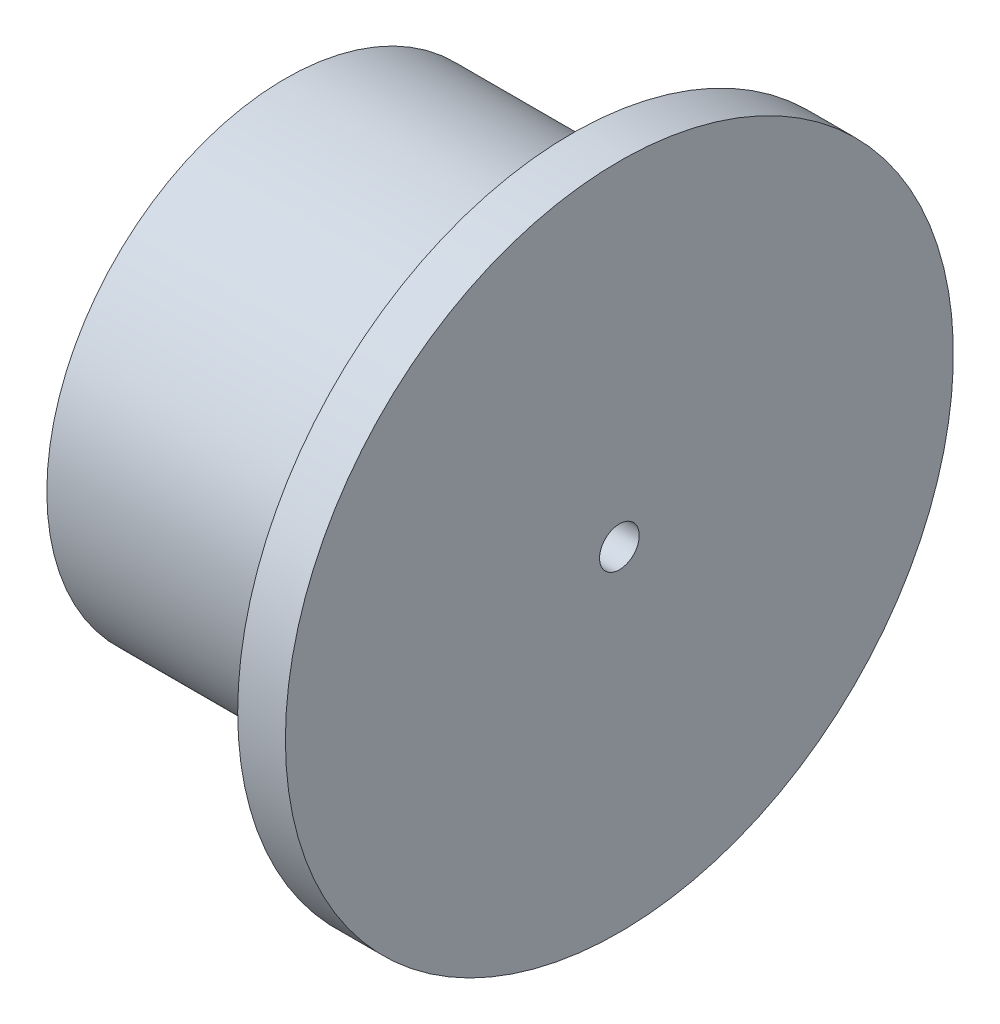
SolidWorks part; units mm, degrees
ref_plane "Front Plane" through (0, 0, 0) normal (0, 0, 1) x (1, 0, 0)
ref_plane "Top Plane" through (0, 0, 0) normal (0, 1, 0) x (1, 0, 0)
ref_plane "Right Plane" through (0, 0, 0) normal (1, 0, 0) x (0, 0, -1)
sketch "Sketch2" plane through (0, 0, 0) normal (0, 0, 1) x (1, 0, 0)
  line L3 (3.81, 25.4) -> (41.91, 25.4)
  line L4 (41.91, 25.4) -> (41.91, 38.1)
  line L5 (41.91, 38.1) -> (48.26, 38.1)
  line L16 (48.26, 38.1) -> (48.26, -6.35)
  line L17 (3.81, 25.4) -> (3.81, -6.35)
  line L18 (3.81, -6.35) -> (48.26, -6.35)
  dimension "D1" = 38.1
  dimension "D2" = 6.35
  dimension "D4" = 12.7
  dimension "D6" = 44.45
revolve "Revolve1" add sketch "Sketch2" angle 360 about L18
sketch "Sketch3" plane through (48.26, 0, 0) normal (1, 0, 0) x (0, 0, -1)
  circle A0 centre (0, -6.35) radius 2.6416
  dimension "D1" = 5.2832
extrude "Cut-Extrude1" cut sketch "Sketch3" against normal through all
equation "\"width_of_film\"= 1.5'a lil more than 35mm"
equation "\"D1@Sketch2\"=\"width_of_film\""
